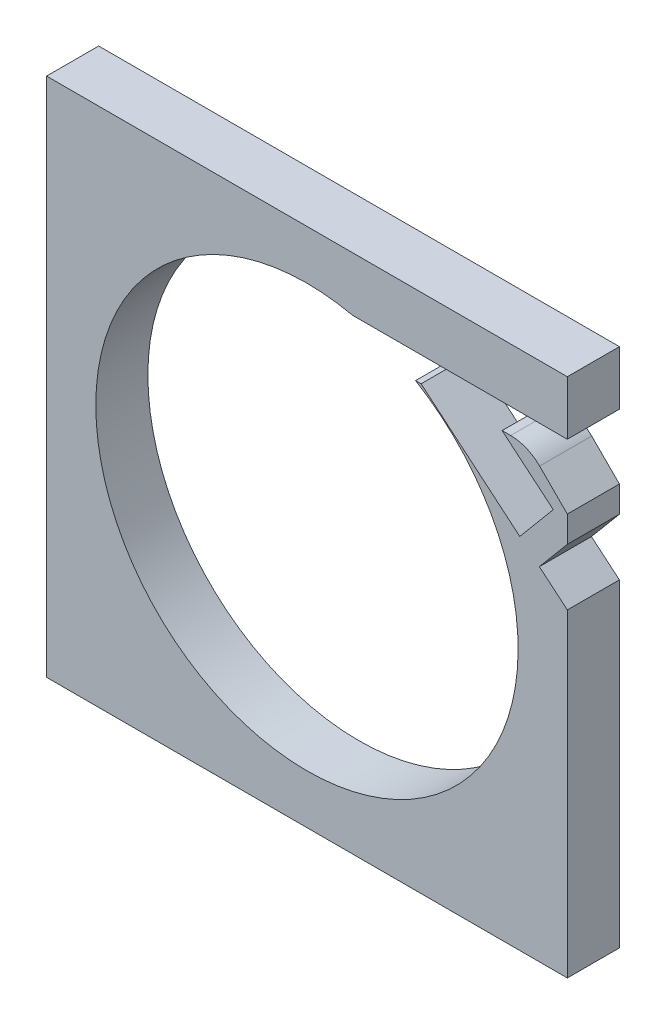
SolidWorks part; units mm, degrees
ref_plane "Front Plane" through (0, 0, 0) normal (0, 0, 1) x (1, 0, 0)
ref_plane "Top Plane" through (0, 0, 0) normal (0, 1, 0) x (1, 0, 0)
ref_plane "Right Plane" through (0, 0, 0) normal (1, 0, 0) x (0, 0, -1)
sketch "Sketch1" plane through (0, 0, 0) normal (0, 0, 1) x (1, 0, 0)
  line L1 (-63.5, 63.5) -> (63.5, 63.5)
  line L2 (-63.5, 63.5) -> (-63.5, -63.5)
  line L3 (-63.5, -63.5) -> (63.5, -63.5)
  line L4 (63.5, 63.5) -> (63.5, -63.5)
  line L5 (-63.5, 63.5) -> (63.5, -63.5) construction
  line L6 (-63.5, -63.5) -> (63.5, 63.5) construction
  point P0 (0, 0)
  dimension "D1" = 127
  dimension "D2" = 127
extrude "Boss-Extrude1" add sketch "Sketch1" along normal blind 12.7
sketch "Sketch2" plane through (0, 0, 12.7) normal (0, 0, 1) x (1, 0, 0)
  circle A0 centre (0, 0) radius 51.5
  dimension "D1" = 103
extrude "Cut-Extrude1" cut sketch "Sketch2" against normal up to next
sketch "Sketch3" plane through (0, 0, 12.7) normal (0, 0, 1) x (1, 0, 0)
  line L0 (0, 51.5) -> (0, 50.2852) construction
  line L1 (0, 50.2852) -> (63.5, 50.2852)
  line L2 (63.5, -63.5) -> (63.5, 63.5) construction
  line L3 (63.5, 50.2852) -> (63.5, 34.4893)
  line L4 (63.5, 34.4893) -> (48.704, 49.2852)
  line L5 (48.704, 49.2852) -> (0, 49.2852)
  line L6 (0, 49.2852) -> (0, 50.2852)
  circle A0 centre (0, 0) radius 51.5 construction
  dimension "D1" = 15.796
  dimension "D2" = 1
  dimension "D3" = 45
extrude "Cut-Extrude2" cut sketch "Sketch3" against normal up to next
sketch "Sketch4" plane through (0, 0, 12.7) normal (0, 0, 1) x (1, 0, 0)
  line L0 (41.4957, 49.2852) -> (60.0752, 33.6952)
  line L1 (14.9404, 49.2852) -> (48.704, 49.2852) construction
  line L2 (56.6769, 19.968) -> (63.5, 28.0994)
  line L3 (60.0752, 33.6952) -> (51.9118, 23.9664)
  line L4 (51.9118, 23.9664) -> (21.738, 49.2852)
  line L5 (41.4957, 49.2852) -> (21.738, 49.2852)
  line L7 (63.5, -63.5) -> (63.5, 34.4893) construction
  line L11 (56.6769, 19.968) -> (63.5, 14.2427)
  line L12 (63.5, 14.2427) -> (63.5, 28.0994)
  dimension "D1" = 12.7
  dimension "D2" = 40
extrude "Cut-Extrude3" cut sketch "Sketch4" against normal up to next
sketch "Sketch5" plane through (0, 0, 12.7) normal (0, 0, 1) x (1, 0, 0)
  line L1 (11.7943, 49.7974) -> (57.1386, 49.7974)
  line L2 (57.1386, 44.1711) -> (19.3611, 44.1711)
  line L3 (19.3611, 44.1711) -> (11.7943, 49.7974)
  line L4 (57.1386, 49.7974) -> (57.1386, 44.1711)
extrude "Cut-Extrude4" cut sketch "Sketch5" against normal through all
fillet "Fillet1" radius 10 1 edges at (53.8182, 44.1711, 6.35)
